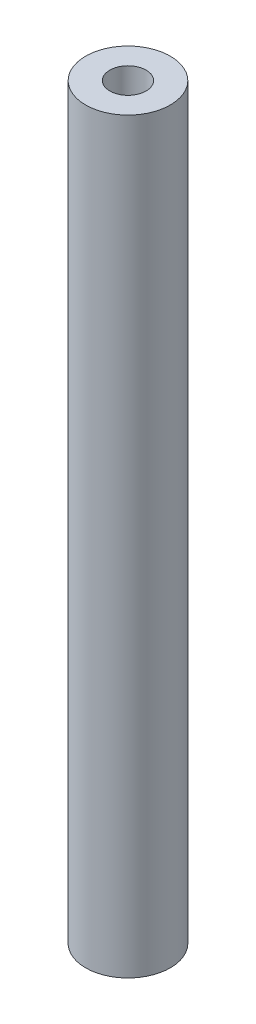
SolidWorks part; units mm, degrees
ref_plane "Front Plane" through (0, 0, 0) normal (0, 0, 1) x (1, 0, 0)
ref_plane "Top Plane" through (0, 0, 0) normal (0, 1, 0) x (1, 0, 0)
ref_plane "Right Plane" through (0, 0, 0) normal (1, 0, 0) x (0, 0, -1)
sketch "Sketch1" plane through (0, 0, 0) normal (0, 1, 0) x (1, 0, 0)
  circle A0 centre (0, 0) radius 1.5
  circle A1 centre (0, 0) radius 3.5
  dimension "D1" = 3
  dimension "D2" = 7
extrude "Boss-Extrude1" add sketch "Sketch1" along normal blind 61.8
